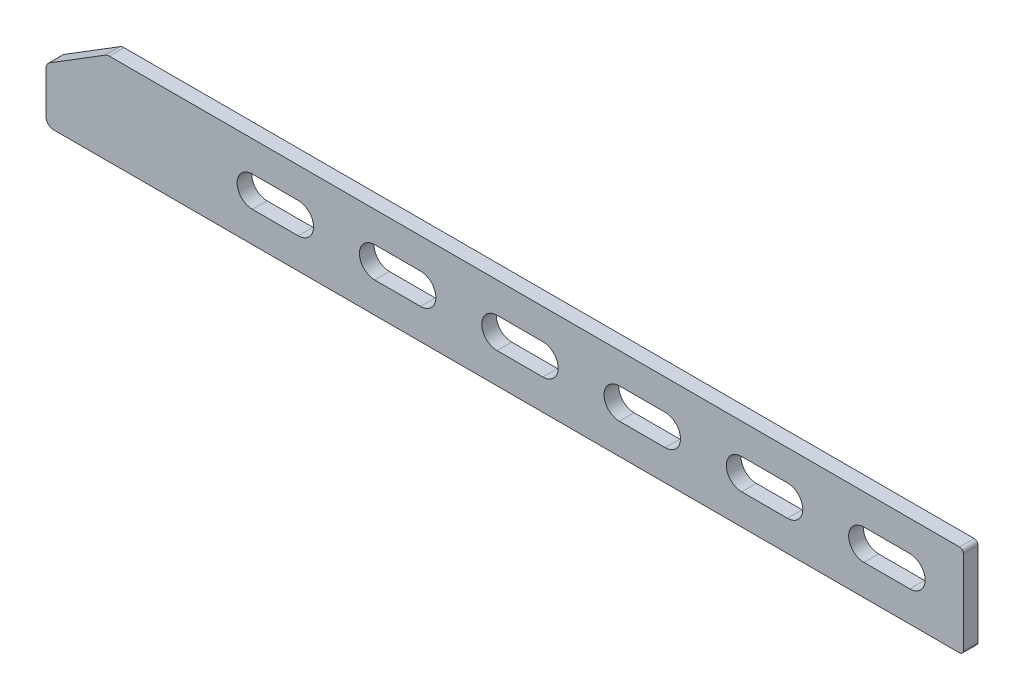
SolidWorks part; units mm, degrees
ref_plane "Front Plane" through (0, 0, 0) normal (0, 0, 1) x (1, 0, 0)
ref_plane "Top Plane" through (0, 0, 0) normal (0, 1, 0) x (1, 0, 0)
ref_plane "Right Plane" through (0, 0, 0) normal (1, 0, 0) x (0, 0, -1)
sketch "Sketch1" plane through (0, 0, 0) normal (0, 0, 1) x (1, 0, 0)
  line L1 (0, 0) -> (-177.8, 0)
  line L2 (0, 0) -> (0, 19.05)
  line L3 (0, 19.05) -> (-177.8, 19.05)
  line L4 (-177.8, 0) -> (-177.8, 19.05)
  dimension "D1" = 19.05
  dimension "D2" = 177.8
extrude "Boss-Extrude1" add sketch "Sketch1" along normal blind 3.048
sketch "Sketch2" plane through (0, 0, 3.048) normal (0, 0, 1) x (1, 0, 0)
  line L0 (-177.8, 9.525) -> (0, 9.525) construction
  line L1 (-177.8, 19.05) -> (-177.8, 0) construction
  line L2 (0, 0) -> (0, 19.05) construction
  line L3 (-11.1125, 9.525) -> (-20.6375, 9.525) construction
  line L4 (-11.1125, 6.35) -> (-20.6375, 6.35)
  line L5 (-11.1125, 12.7) -> (-20.6375, 12.7)
  line L6 (-36.5125, 9.525) -> (-46.0375, 9.525) construction
  line L7 (-36.5125, 6.35) -> (-46.0375, 6.35)
  line L8 (-36.5125, 12.7) -> (-46.0375, 12.7)
  line L9 (-61.9125, 9.525) -> (-71.4375, 9.525) construction
  line L10 (-61.9125, 6.35) -> (-71.4375, 6.35)
  line L11 (-61.9125, 12.7) -> (-71.4375, 12.7)
  line L12 (-87.3125, 9.525) -> (-96.8375, 9.525) construction
  line L13 (-87.3125, 6.35) -> (-96.8375, 6.35)
  line L14 (-87.3125, 12.7) -> (-96.8375, 12.7)
  line L15 (-112.7125, 9.525) -> (-122.2375, 9.525) construction
  line L16 (-112.7125, 6.35) -> (-122.2375, 6.35)
  line L17 (-112.7125, 12.7) -> (-122.2375, 12.7)
  line L18 (-138.1125, 9.525) -> (-147.6375, 9.525) construction
  line L19 (-138.1125, 6.35) -> (-147.6375, 6.35)
  line L20 (-138.1125, 12.7) -> (-147.6375, 12.7)
  arc A0 (-11.1125, 6.35) -> (-11.1125, 12.7) centre (-11.1125, 9.525) ccw
  arc A1 (-20.6375, 12.7) -> (-20.6375, 6.35) centre (-20.6375, 9.525) ccw
  arc A2 (-36.5125, 6.35) -> (-36.5125, 12.7) centre (-36.5125, 9.525) ccw
  arc A3 (-46.0375, 12.7) -> (-46.0375, 6.35) centre (-46.0375, 9.525) ccw
  arc A4 (-61.9125, 6.35) -> (-61.9125, 12.7) centre (-61.9125, 9.525) ccw
  arc A5 (-71.4375, 12.7) -> (-71.4375, 6.35) centre (-71.4375, 9.525) ccw
  arc A6 (-87.3125, 6.35) -> (-87.3125, 12.7) centre (-87.3125, 9.525) ccw
  arc A7 (-96.8375, 12.7) -> (-96.8375, 6.35) centre (-96.8375, 9.525) ccw
  arc A8 (-112.7125, 6.35) -> (-112.7125, 12.7) centre (-112.7125, 9.525) ccw
  arc A9 (-122.2375, 12.7) -> (-122.2375, 6.35) centre (-122.2375, 9.525) ccw
  arc A10 (-138.1125, 6.35) -> (-138.1125, 12.7) centre (-138.1125, 9.525) ccw
  arc A11 (-147.6375, 12.7) -> (-147.6375, 6.35) centre (-147.6375, 9.525) ccw
  point P8 (-15.875, 9.525)
  point P16 (-41.275, 9.525)
  point P23 (-66.675, 9.525)
  point P30 (-92.075, 9.525)
  point P37 (-117.475, 9.525)
  point P44 (-142.875, 9.525)
  dimension "D2" = 3.175
  dimension "D1" = 9.525
  dimension "D3" = 15.875
  dimension "D4" = 6
extrude "Cut-Extrude1" cut sketch "Sketch2" against normal through all
sketch "Sketch3" plane through (0, 0, 0) normal (0, 0, -1) x (-1, 0, 0)
  line L0 (177.8, 0) -> (190.5, 0)
  line L1 (190.5, 0) -> (190.5, 11.176)
  line L2 (190.5, 11.176) -> (177.8, 19.05)
  line L3 (177.8, 19.05) -> (177.8, 0)
  dimension "D1" = 12.7
  dimension "D2" = 11.176
extrude "Boss-Extrude2" add sketch "Sketch3" against normal up to surface (3.048 mm away) up to face at (-142.875, 9.525, 3.048)
fillet "Fillet1" radius 1.5875 3 edges at (-190.5, 0, 1.524) (-190.5, 11.176, 1.524) (-177.8, 19.05, 1.524)
fillet "Fillet2" radius 0.7937 2 edges at (0, 19.05, 1.524) (0, 0, 1.524)
